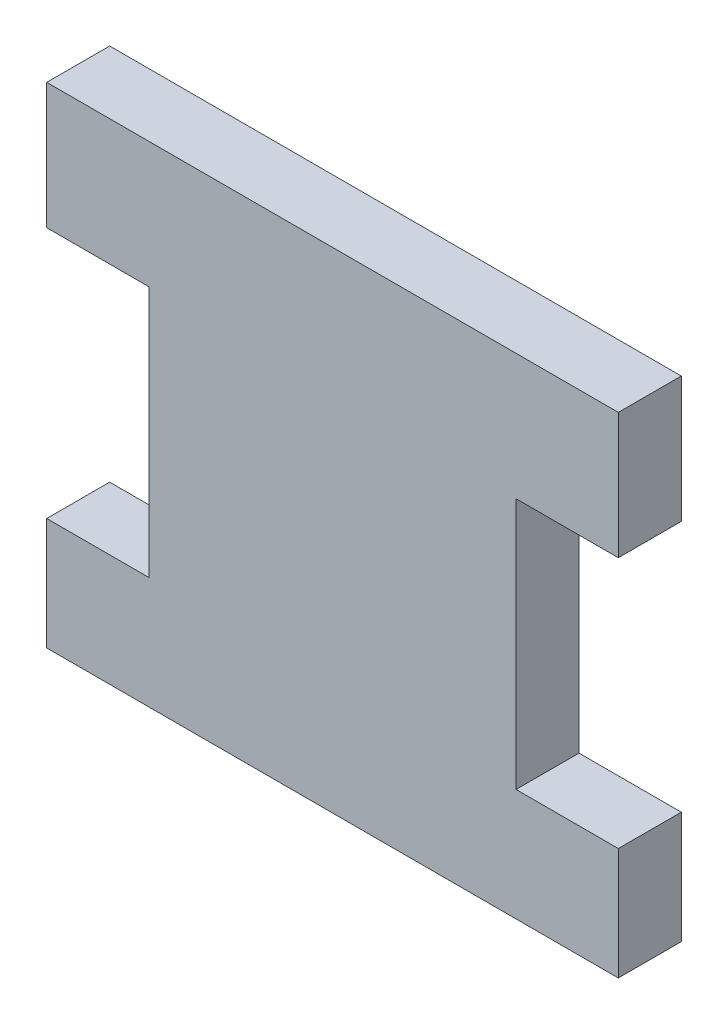
SolidWorks part; units mm, degrees
material "Oak"
ref_plane "Front Plane" through (0, 0, 0) normal (0, 0, 1) x (1, 0, 0)
ref_plane "Top Plane" through (0, 0, 0) normal (0, 1, 0) x (1, 0, 0)
ref_plane "Right Plane" through (0, 0, 0) normal (1, 0, 0) x (0, 0, -1)
sketch "Sketch1" plane through (0, 0, 0) normal (0, 0, 1) x (1, 0, 0)
  line L0 (0, 0) -> (0, 1532.5224) construction
  line L1 (1.135, -0.9141) -> (-1.135, -0.9141)
  line L2 (-1.135, -0.9141) -> (-1.135, -0.4687)
  line L3 (1.135, -0.9141) -> (1.135, -0.4687)
  line L4 (-1.135, -0.4687) -> (-0.7288, -0.4687)
  line L5 (1.135, -0.4687) -> (0.7288, -0.4687)
  line L6 (-0.7288, -0.4687) -> (-0.7288, 0.5313)
  line L7 (0.7288, -0.4687) -> (0.7288, 0.5313)
  line L8 (-0.7288, 0.5313) -> (-1.135, 0.5313)
  line L9 (0.7288, 0.5313) -> (1.135, 0.5313)
  line L10 (-1.135, 0.5313) -> (-1.135, 1.0313)
  line L11 (1.135, 0.5313) -> (1.135, 1.0313)
  line L12 (-1.135, 1.0313) -> (1.135, 1.0313)
  point P6 (0, -0.9141)
  point P16 (0, 1.0313)
  dimension "D1" = 0.5
  dimension "D2" = 2.27
  dimension "D3" = 1
extrude "Boss-Extrude1" add sketch "Sketch1" along normal blind 0.25
